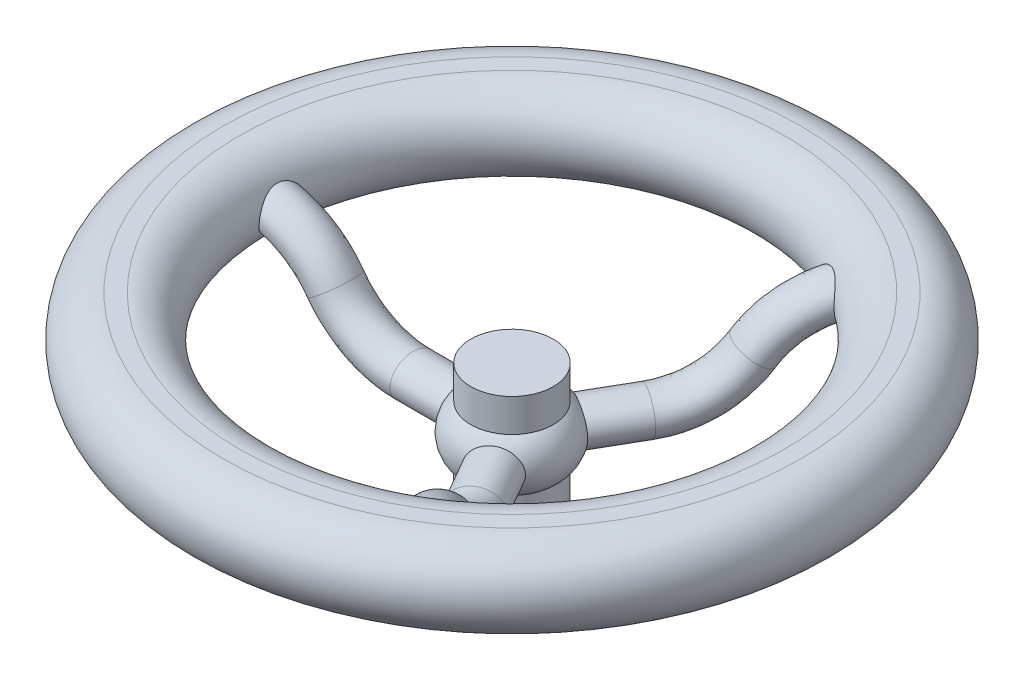
SolidWorks part; units mm, degrees
ref_plane "정면" through (0, 0, 0) normal (0, 0, 1) x (1, 0, 0)
ref_plane "윗면" through (0, 0, 0) normal (0, 1, 0) x (1, 0, 0)
ref_plane "우측면" through (0, 0, 0) normal (1, 0, 0) x (0, 0, -1)
sketch "스케치1" plane through (0, 0, 0) normal (0, 0, 1) x (1, 0, 0)
  line L0 (-12.5, 35) -> (-12.5, 45)
  line L1 (0, 0) -> (-12.5, 0)
  line L2 (0, 0) -> (0, 45) construction
  line L3 (0, 45) -> (-12.5, 45)
  line L4 (-12.5, 0) -> (-12.5, 19)
  line L5 (0, 0) -> (0, 45)
  arc A0 (-12.5, 19) -> (-12.5, 35) centre (-6.5, 27) cw
  point P8 (0, 0)
  point P9 (-16.5, 27)
  dimension "D4" = 10
  dimension "D5" = 4
  dimension "D1" = 45
  dimension "D2" = 25
  dimension "D3" = 16
revolve "회전1" add sketch "스케치1" angle 360 about L2
sketch "스케치2" plane through (0, 0, 0) normal (0, 0, 1) x (1, 0, 0)
  line L0 (-87.5, 51) -> (-82.5, 51) construction
  line L1 (-87.5, 63.5) -> (-82.5, 63.5)
  line L2 (-87.5, 38.5) -> (-82.5, 38.5)
  line L5 (12.5, 45) -> (-12.5, 45) construction
  arc A0 (-87.5, 63.5) -> (-87.5, 38.5) centre (-87.5, 51) ccw
  arc A1 (-82.5, 38.5) -> (-82.5, 63.5) centre (-82.5, 51) ccw
  point P2 (-85, 51)
  point P9 (0, 0)
  point P10 (0, 0)
  point P11 (0, 0)
  point P12 (0, 0)
  point P13 (0, 0)
  point P14 (-87.5, 51)
  point P17 (-87.5, 51)
  point P19 (132.8372, -0.1246)
  point P20 (62.1006, 5.9002)
  point P21 (-82.5, 51)
  point P22 (0, 0)
  dimension "D1" = 25
  dimension "D2" = 30
  dimension "D3" = 6
  dimension "D4" = 85
revolve "회전2" add sketch "스케치2" angle 360
sketch "스케치3" plane through (0, 0, 0) normal (0, 0, 1) x (1, 0, 0)
  line L0 (0, 27) -> (-30, 27)
  line L1 (-76.9894, 51) -> (-85, 51)
  line L2 (0, 0) -> (0, 45) construction
  arc A0 (-30, 27) -> (-53.4947, 39) centre (-30, 56) cw
  arc A1 (-53.4947, 39) -> (-76.9894, 51) centre (-76.9894, 22) ccw
  point P6 (0, 0)
  point P9 (0, 0)
  point P10 (0, 0)
  point P11 (0, 0)
  point P12 (-85, 51.277)
  point P13 (0, 0)
  point P14 (0, 0)
  point P15 (-85, 51.277)
  point P16 (0, 26.6858)
  point P19 (0, 26.9793)
  dimension "D2" = 29
  dimension "D1" = 55
sketch "스케치4" plane through (0, 0, 0) normal (1, 0, 0) x (0, 0, -1)
  ellipse E0 centre (0, 27) end of major axis (7, 27) minor radius 6
  point P1 (0, 0)
  point P7 (37.9762, 23.2047)
  point P8 (0, 0)
  point P9 (0, 0)
  point P10 (49.3897, 30.3829)
  dimension "D1" = 14
  dimension "D2" = 12
sweep "스윕1" add profiles "스케치4" path "스케치3"
pattern_circular "원형 패턴1" count 3 over 360 about axis through (0, 45, 0) along (0, -1, 0) of "스윕1"
